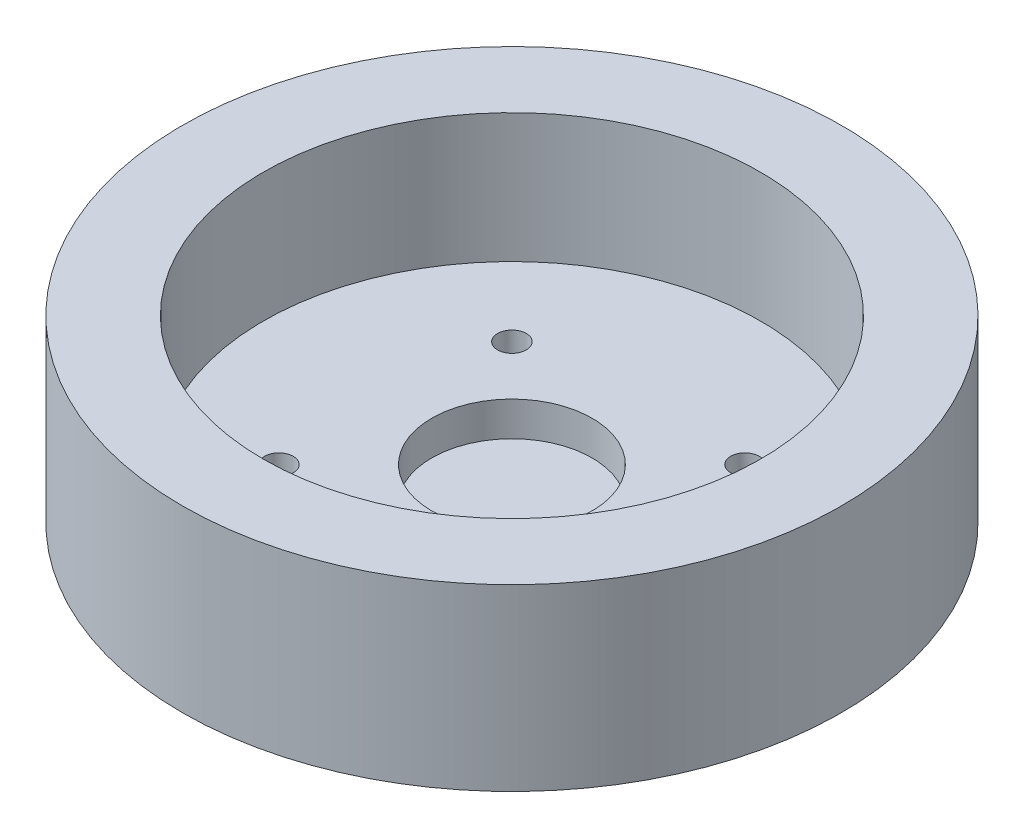
SolidWorks part; units mm, degrees
ref_plane "前视基准面" through (0, 0, 0) normal (0, 0, 1) x (1, 0, 0)
ref_plane "上视基准面" through (0, 0, 0) normal (0, 1, 0) x (1, 0, 0)
ref_plane "右视基准面" through (0, 0, 0) normal (1, 0, 0) x (0, 0, -1)
sketch "草图1" plane through (0, 0, 0) normal (0, 1, 0) x (1, 0, 0)
  circle A0 centre (0, 0) radius 16.35
  circle A1 centre (0, 0) radius 5.6
  circle A2 centre (0, 0) radius 15 construction
  circle A3 centre (0, 0) radius 23
  circle A4 centre (0, 0) radius 17.35
  dimension "D1" = 32.7
  dimension "D2" = 11.2
  dimension "D3" = 30
  dimension "D4" = 46
  dimension "D5" = 34.7
extrude "凸台-拉伸1" add sketch "草图1" along normal blind 3.5 contours A1 | A4
sketch "草图3" plane through (0, 0, 0) normal (0, 1, 0) x (1, 0, 0)
  circle A0 centre (0, 0) radius 23 construction
  circle A1 centre (0, 0) radius 23
  circle A2 centre (0, 0) radius 17.35 construction
  circle A3 centre (0, 0) radius 17.35
  dimension "D1" = 46
extrude "凸台-拉伸3" add sketch "草图3" along normal blind 12.5
sketch "草图4" plane through (0, 0, 0) normal (0, 1, 0) x (1, 0, 0)
  circle A0 centre (0, 0) radius 5.6 construction
  circle A1 centre (0, 0) radius 5.6
extrude "凸台-拉伸4" add sketch "草图4" along normal blind 1.1
sketch "草图6" plane through (0, 0, 0) normal (0, 1, 0) x (1, 0, 0)
  line L0 (-23.1107, 23.1107) -> (0, 0) construction
  line L1 (0, 0) -> (22.5537, 22.5537) construction
  circle A0 centre (0, 0) radius 16.35 construction
  circle A1 centre (0, 0) radius 16.35 construction
  circle A2 centre (0, 0) radius 17.35 construction
  circle A3 centre (0, 0) radius 17.35 construction
  circle A4 centre (8.1317, 8.1317) radius 1
  circle A5 centre (7.4246, -7.4246) radius 1
  circle A6 centre (-8.1317, -8.1317) radius 1
  circle A7 centre (-7.4246, 7.4246) radius 1
  circle A8 centre (0, 0) radius 5.6 construction
  circle A9 centre (0, 0) radius 5.6 construction
  dimension "D1" = 32.7
  dimension "D2" = 34.7
  dimension "D3" = 2
  dimension "D4" = 2
  dimension "D5" = 2
  dimension "D6" = 2
  dimension "D7" = 11.2
  dimension "D8" = 10.5
  dimension "D9" = 10.5
  dimension "D10" = 11.5
  dimension "D11" = 11.5
extrude "切除-拉伸3" cut sketch "草图6" against normal mid plane 10
sketch "草图8" plane through (0, 0, 0) normal (0, -1, 0) x (1, 0, 0)
  circle A0 centre (-8.1317, 8.1317) radius 1 construction
  circle A1 centre (-8.1317, 8.1317) radius 1 construction
  circle A2 centre (-8.1317, 8.1317) radius 1.91
  circle A3 centre (7.4246, 7.4246) radius 1.91
  circle A4 centre (-7.4246, -7.4246) radius 1.91
  circle A5 centre (8.1317, -8.1317) radius 1.91
  dimension "D1" = 3.82
  dimension "D2" = 3.82
  dimension "D3" = 3.82
  dimension "D4" = 3.82
extrude "切除-拉伸4" cut sketch "草图8" against normal blind 1.9
